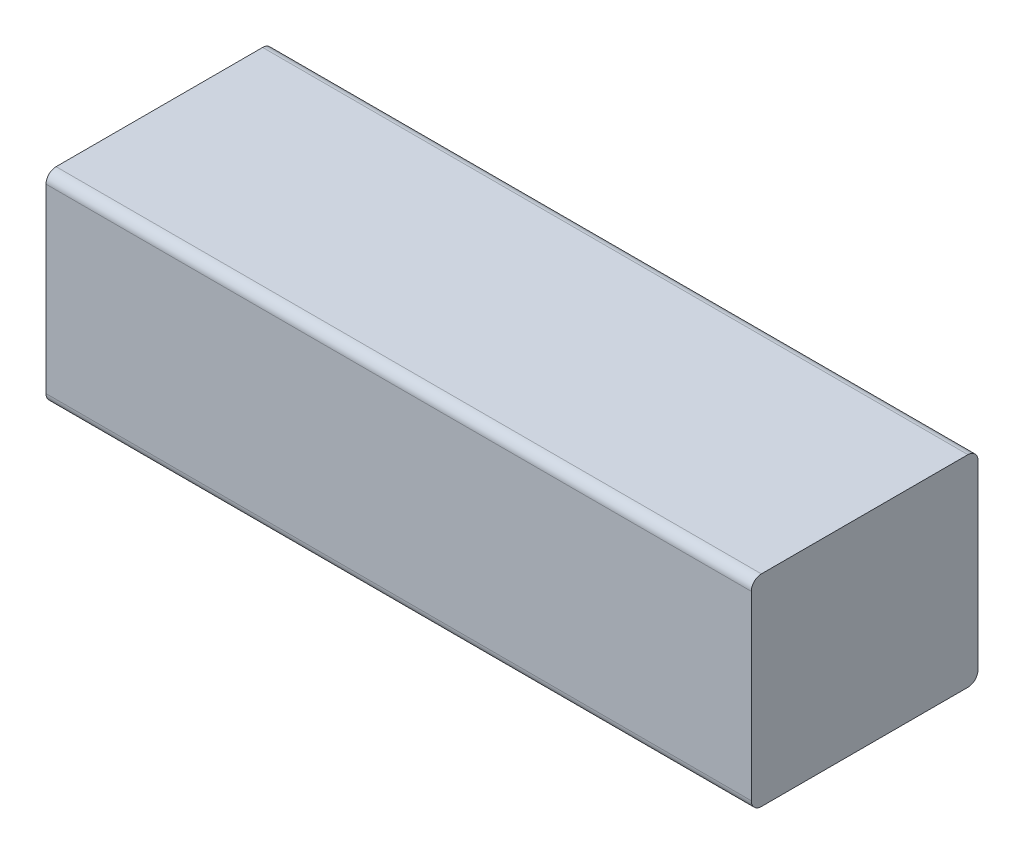
SolidWorks part; units mm, degrees
ref_plane "Plan de face" through (0, 0, 0) normal (0, 0, 1) x (1, 0, 0)
ref_plane "Plan de dessus" through (0, 0, 0) normal (0, 1, 0) x (1, 0, 0)
ref_plane "Plan de droite" through (0, 0, 0) normal (1, 0, 0) x (0, 0, -1)
sketch "Esquisse1" plane through (0, 0, 0) normal (0, 1, 0) x (1, 0, 0)
  line L0 (0, 0) -> (140, 0)
  line L1 (140, 0) -> (140, 45)
  line L2 (140, 45) -> (0, 45)
  line L3 (0, 45) -> (0, 0)
extrude "Boss.-Extru.1" add sketch "Esquisse1" along normal blind 40
fillet "Congé1" radius 2 4 edges at (70, 0, -45) (70, 0, 0) (70, 40, -45) (70, 40, 0)
